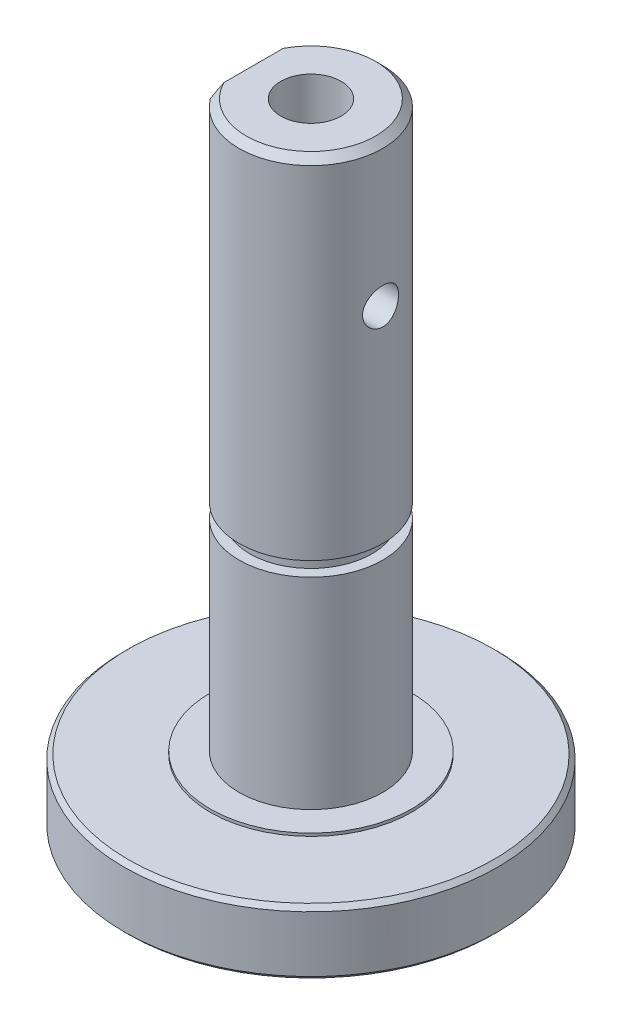
SolidWorks part; units mm, degrees
material "AISI 1045 钢，冷拔"
ref_plane "前视基准面" through (0, 0, 0) normal (0, 0, 1) x (1, 0, 0)
ref_plane "上视基准面" through (0, 0, 0) normal (0, 1, 0) x (1, 0, 0)
ref_plane "右视基准面" through (0, 0, 0) normal (1, 0, 0) x (0, 0, -1)
ref_plane "基准面1" through (0, 0, 0) normal (0, 0, -1) x (-1, 0, 0)
sketch "草图1" plane through (0, 0, 0) normal (0, 0, -1) x (-1, 0, 0)
  line L0 (-13, 0) -> (0, 0)
  line L1 (0, 0) -> (0, 44)
  line L2 (0, 44) -> (-5, 44)
  line L3 (-5, 44) -> (-5, 19.7)
  line L4 (-5, 19.7) -> (-4.25, 19.7)
  line L5 (-4.25, 19.7) -> (-4.25, 18.7)
  line L6 (-4.25, 18.7) -> (-5, 18.7)
  line L7 (-5, 18.7) -> (-5, 4.7)
  line L8 (-5, 4.7) -> (-7, 4.7)
  line L9 (-7, 4.7) -> (-7, 4.5)
  line L10 (-7, 4.5) -> (-13, 4.5)
  line L11 (-13, 4.5) -> (-13, 0)
  line L12 (0, 0) -> (0, 44) construction
revolve "旋转1" add sketch "草图1" angle 360 about L12
sketch "草图2" plane through (0, 44, 0) normal (0, 1, 0) x (-1, 0, 0)
  line L0 (4, 3) -> (4, -3)
  arc A0 (4, -3) -> (4, 3) centre (0, 0) ccw
extrude "切除-拉伸1" cut sketch "草图2" against normal blind 20
hole_wizard "Ø4.2 (4.2) 直径孔1" positions "草图4" profile "草图3" hole size "Ø4.2" standard "ANSI Metric"
sketch "草图4" plane through (0, 44, 0) normal (0, 1, 0) x (1, 0, 0)
  point P0 (0, 0)
sketch "草图3" plane through (0, 44, 0) normal (1, 0, 0) x (0, 0, 1)
  line L0 (0, 0) -> (0, 15.2618)
  line L1 (0, 15.2618) -> (2.1, 14)
  line L2 (2.1, 14) -> (2.1, 0)
  line L5 (2.1, 0) -> (0, 0)
  line L10 (0, 15.2618) -> (-2.1, 14) construction
  line L11 (0, -6.35) -> (0, 107.95) construction
  dimension "孔直径" = 4.2
  dimension "孔深度" = 14
  dimension "导头角度" = 118
hole_wizard "Ø2.5 (2.5) 直径孔1" positions "草图6" profile "草图5" hole size "Ø2.5" standard "ANSI Metric"
sketch "草图6" plane through (-4, 0, 0) normal (-1, 0, 0) x (0, 0, 1)
  point P0 (0, 34)
sketch "草图5" plane through (-4, 34, 0) normal (0, 1, 0) x (0, 0, 1)
  line L0 (0, 0) -> (0, 12.3125)
  line L1 (0, 12.3125) -> (1.25, 12.3125)
  line L2 (1.25, 12.3125) -> (1.25, 0)
  line L5 (1.25, 0) -> (0, 0)
  line L10 (0, 12.3125) -> (-1.25, 12.3125) construction
  line L11 (0, -6.35) -> (0, 107.95) construction
  dimension "孔直径" = 2.5
  dimension "孔深度" = 12.3125
  dimension "导头角度" = 180
chamfer "倒角1" distance 0.3 angle 45 2 edges at (0, 4.5, 13) (0, 0, 13)
chamfer "倒角2" distance 0.5 angle 45 1 edges at (5, 44, 0)
